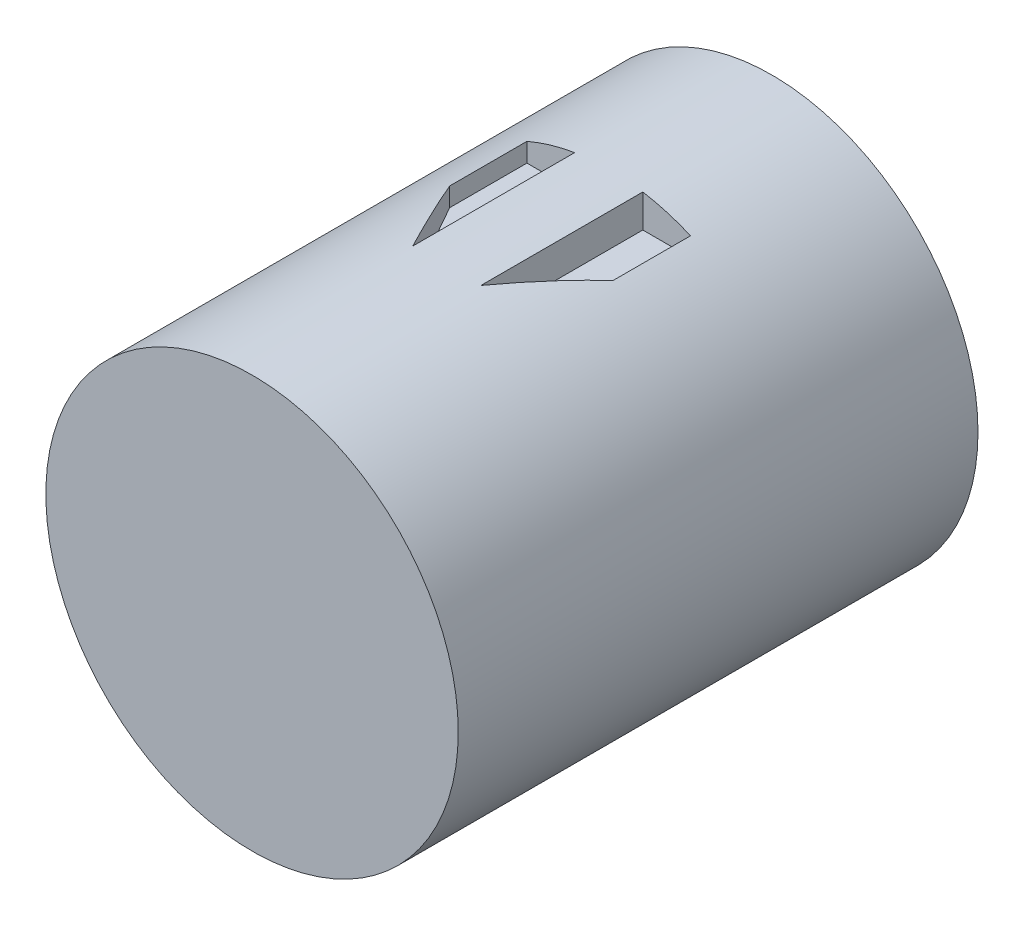
SolidWorks part; units mm, degrees
material "AISI 1010 Steel, hot rolled bar"
ref_plane "Alzado" through (0, 0, 0) normal (0, 0, 1) x (1, 0, 0)
ref_plane "Planta" through (0, 0, 0) normal (0, 1, 0) x (1, 0, 0)
ref_plane "Vista lateral" through (0, 0, 0) normal (1, 0, 0) x (0, 0, -1)
sketch "Sketch1" plane through (0, 0, 0) normal (0, 0, 1) x (1, 0, 0)
  circle A0 centre (0, 0) radius 12.1
  dimension "D1" = 24.2
extrude "Boss-Extrude1" add sketch "Sketch1" along normal blind 30.5
ref_plane "Plane1" through (0, 10, 0) normal (0, 1, 0) x (1, 0, 0)
sketch "Sketch2" plane through (0, 10, 0) normal (0, 1, 0) x (1, 0, 0)
  line L0 (0, 0) -> (0, -30.5) construction
  line L1 (-12.1, -30.5) -> (12.1, -30.5) construction
  line L6 (-2, -9.5692) -> (-4.8, -9.5692)
  line L7 (-4.8, -9.5692) -> (-4.8, -14.1043)
  line L8 (-4.8, -14.1043) -> (-2, -19.0692)
  line L9 (-2, -19.0692) -> (-2, -9.5692)
  line L10 (4.8, -14.1043) -> (2, -19.0692)
  line L11 (4.8, -9.5692) -> (4.8, -14.1043)
  line L12 (2, -9.5692) -> (4.8, -9.5692)
  line L13 (2, -19.0692) -> (2, -9.5692)
  dimension "D1" = 2
  dimension "D2" = 2.8
  dimension "D3" = 9.5
  dimension "D4" = 5.7
extrude "Cut-Extrude1" cut sketch "Sketch2" along normal through all
